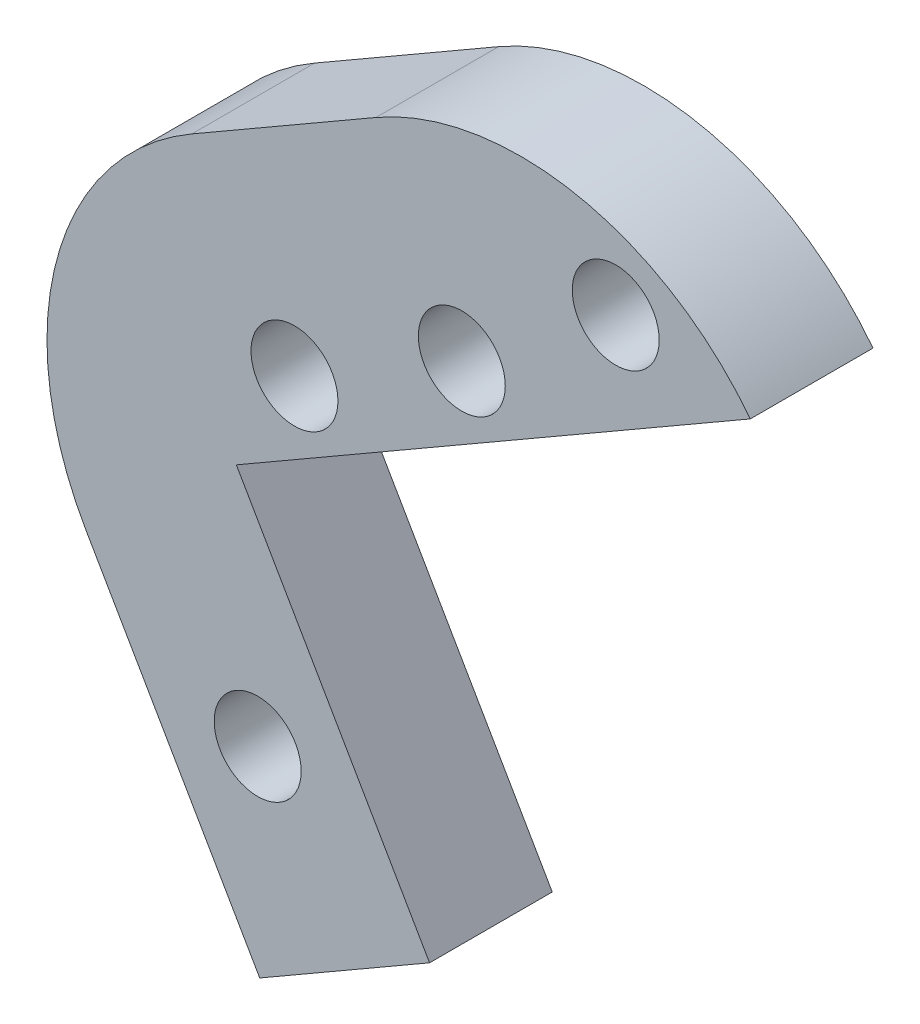
SolidWorks part; units mm, degrees
material "Erable"
ref_plane "Plan de face" through (0, 0, 0) normal (0, 0, 1) x (1, 0, 0)
ref_plane "Plan de dessus" through (0, 0, 0) normal (0, 1, 0) x (1, 0, 0)
ref_plane "Plan de droite" through (0, 0, 0) normal (1, 0, 0) x (0, 0, -1)
sketch "Esquisse3" plane through (0, 0, 0) normal (0, 0, 1) x (1, 0, 0)
  line L0 (0, -3.4925) -> (0, 3.4925) construction
  line L1 (-54.6725, 55) -> (54.6725, 55)
  line L2 (-77.5, 12.5385) -> (-77.5, -12.5385)
  line L3 (-54.6725, -55) -> (54.6725, -55)
  line L4 (77.5, 12.5385) -> (77.5, -12.5385)
  line L5 (3.4925, 0) -> (-3.4925, 0) construction
  line L6 (-54.6725, 55) -> (-71.993, 85)
  line L7 (-71.993, 85) -> (-107.5, 64.5)
  line L8 (-107.5, 64.5) -> (-77.5, 12.5385)
  line L9 (-77.5, -12.5385) -> (-107.5, -64.5)
  line L10 (-107.5, -64.5) -> (-71.993, -85)
  line L11 (-71.993, -85) -> (-54.6725, -55)
  line L12 (54.6725, 55) -> (71.993, 85)
  line L13 (71.993, 85) -> (107.5, 64.5)
  line L14 (107.5, 64.5) -> (77.5, 12.5385)
  line L15 (77.5, -12.5385) -> (107.5, -64.5)
  line L16 (107.5, -64.5) -> (71.993, -85)
  line L17 (71.993, -85) -> (54.6725, -55)
  line L19 (-26.875, 36.6667) -> (26.875, 36.6667)
  line L20 (-26.875, 36.6667) -> (-26.875, -36.6667)
  line L21 (-26.875, -36.6667) -> (26.875, -36.6667)
  line L22 (26.875, 36.6667) -> (26.875, -36.6667)
  point P4 (0, 55)
  point P7 (-77.5, 0)
  point P24 (0, -36.6667)
  point P27 (26.875, 0)
  dimension "D3" = 120
  dimension "D6" = 41
  dimension "D7" = 120
  dimension "D8" = 120
  dimension "D9" = 120
  dimension "D2" = 110
  dimension "D10" = 53.75
  dimension "D11" = 73.3333
  dimension "D4" = 170
  dimension "D5" = 215
  dimension "D12" = 60
extrude "Boss.-Extru.2" add sketch "Esquisse3" against normal blind 6.35 separate body
fillet "Congé6" radius 20 12 edges at (77.5, -12.5385, -3.175) (77.5, 12.5385, -3.175) (54.6725, 55, -3.175) (-54.6725, 55, -3.175) (-77.5, 12.5385, -3.175) (-77.5, -12.5385, -3.175) (-54.6725, -55, -3.175) (54.6725, -55, -3.175) (26.875, -36.6667, -3.175) (26.875, 36.6667, -3.175) (-26.875, -36.6667, -3.175) (-26.875, 36.6667, -3.175)
fillet "Congé7" radius 15 8 edges at (71.993, -85, -3.175) (107.5, -64.5, -3.175) (107.5, 64.5, -3.175) (71.993, 85, -3.175) (-71.993, 85, -3.175) (-107.5, 64.5, -3.175) (-71.993, -85, -3.175) (-107.5, -64.5, -3.175)
sketch "Esquisse4" plane through (0, 0, 0) normal (0, 0, 1) x (1, 0, 0)
  line L0 (-53.2831, 32.2936) -> (-74.2831, 68.6667)
  line L1 (-74.2831, 68.6667) -> (-92.2098, 58.3167)
  line L2 (-92.2098, 58.3167) -> (-71.2098, 21.9436)
  line L3 (-71.2098, 21.9436) -> (-53.2831, 32.2936)
  line L4 (-83.2465, 63.4917) -> (-89.7465, 74.75) construction
  line L5 (-84.9833, 77.5) -> (-94.5096, 72) construction
  line L6 (-60.446, 65) -> (-64.493, 72.0096) construction
  line L7 (-49.7465, 5.468) -> (-52.7465, 10.6641) construction
  line L8 (-51.695, 4.343) -> (-54.695, 9.5391)
  line L9 (-47.7979, 6.593) -> (-50.7979, 11.7891)
  line L10 (-56.2914, 26.804) -> (-80.5414, 68.8063) construction
  line L11 (-80.5414, 68.8063) -> (-89.2016, 63.8063) construction
  line L12 (-89.2016, 63.8063) -> (-64.9516, 21.804) construction
  line L13 (-64.9516, 21.804) -> (-56.2914, 26.804) construction
  line L14 (-81.7098, 40.1301) -> (-77.0766, 42.8051) construction
  arc A0 (-51.695, 4.343) -> (-47.7979, 6.593) centre (-49.7465, 5.468) ccw
  arc A1 (-50.7979, 11.7891) -> (-54.695, 9.5391) centre (-52.7465, 10.6641) ccw
  circle A3 centre (-56.2914, 26.804) radius 2.25
  circle A4 centre (-64.9516, 21.804) radius 2.25
  circle A5 centre (-89.2016, 63.8063) radius 2.25
  circle A6 centre (-80.5414, 68.8063) radius 2.25
  point P12 (-51.2465, 8.066)
  point P23 (-84.8715, 66.3063)
  dimension "D5" = 2.25
  dimension "D7" = 48.5
  dimension "D9" = 4.5
  dimension "D1" = 20.7
  dimension "D2" = 42
  dimension "D3" = 13
  dimension "D4" = 19
  dimension "D6" = 6
  dimension "D8" = 10
extrude "Enlèv. mat.-Extru.2" cut sketch "Esquisse4" against normal blind 6.35
mirror "Symétrie1" about plane through (0, 0, 0) normal (0, 1, 0) of "Enlèv. mat.-Extru.2"
mirror "Symétrie2" about plane through (0, 0, 0) normal (1, 0, 0) of "Symétrie1", "Enlèv. mat.-Extru.2"
sketch "Esquisse5" plane through (0, 0, 0) normal (0, 0, 1) x (1, 0, 0)
  line L0 (0, -3.4925) -> (0, 3.4925) construction
  line L1 (-33, 48) -> (33, 48) construction
  line L2 (-33, 48) -> (-33, -48) construction
  line L3 (-33, -48) -> (33, -48) construction
  line L4 (33, 48) -> (33, -48) construction
  line L5 (3.4925, 0) -> (-3.4925, 0) construction
  point P6 (0, 48)
  point P7 (-33, 0)
  dimension "D1" = 66
  dimension "D2" = 96
hole_wizard "Diamètre du perçage Ø4.0 (4)1" positions "Esquisse6" profile "Esquisse7" hole size "Ø4.0" standard "Ansi Metric" end condition through all
sketch "Esquisse6" plane through (0, 0, 0) normal (0, 0, 1) x (1, 0, 0)
  point P0 (33, 48)
  point P3 (-33, 48)
  point P6 (-33, -48)
  point P9 (33, -48)
sketch "Esquisse7" plane through (33, 48, 0) normal (1, 0, 0) x (0, -1, 0)
  line L0 (0, 0) -> (0, 6.35)
  line L1 (0, 6.35) -> (2, 6.35)
  line L2 (2, 6.35) -> (2, 0)
  line L5 (2, 0) -> (0, 0)
  line L11 (0, -6.35) -> (0, 107.95) construction
  dimension "Diamètre du perçage jusqu'au prochain" = 4
  dimension "Profondeur du perçage jusqu'au prochain" = 6.35
sketch "Esquisse8" plane through (0, 0, 0) normal (0, 0, 1) x (1, 0, 0)
  line L1 (-102.0096, 79.5096) -> (102.0096, 79.5096) construction
  line L2 (-102.0096, 79.5096) -> (-102.0096, -79.5096) construction
  line L3 (-102.0096, -79.5096) -> (102.0096, -79.5096) construction
  line L4 (102.0096, 79.5096) -> (102.0096, -79.5096) construction
  arc A0 (94.5096, -72) -> (100, -51.5096) centre (87.0096, -59.0096) ccw construction
  arc A1 (64.493, -72.0096) -> (84.9833, -77.5) centre (77.4833, -64.5096) ccw construction
  arc A2 (-64.493, 72.0096) -> (-84.9833, 77.5) centre (-77.4833, 64.5096) ccw construction
  arc A3 (-94.5096, 72) -> (-100, 51.5096) centre (-87.0096, 59.0096) ccw construction
  dimension "D1" = 204.0192
  dimension "D2" = 159.0192
sketch "Esquisse9" plane through (0, 0, 0) normal (0, 0, 1) x (1, 0, 0)
  line L0 (-65.6089, 73.6747) -> (-92.2098, 58.3167)
  line L1 (-92.2098, 58.3167) -> (-82.2098, 40.9962)
  line L2 (-92.2098, 58.3167) -> (-71.2098, 21.9436) construction
  line L3 (-82.2098, 40.9962) -> (-91, 35.9212)
  line L4 (-100, 51.5096) -> (-80.1795, 17.1795) construction
  line L5 (-91, 35.9212) -> (-100, 51.5096)
  line L6 (-84.9833, 77.5) -> (-94.5096, 72) construction
  line L7 (-84.9833, 77.5) -> (-94.5096, 72)
  line L8 (-74.2831, 68.6667) -> (-92.2098, 58.3167) construction
  arc A0 (-94.5096, 72) -> (-100, 51.5096) centre (-87.0096, 59.0096) ccw construction
  arc A1 (-94.5096, 72) -> (-100, 51.5096) centre (-87.0096, 59.0096) ccw
  arc A2 (-64.493, 72.0096) -> (-84.9833, 77.5) centre (-77.4833, 64.5096) ccw construction
  arc A3 (-65.6089, 73.6747) -> (-84.9833, 77.5) centre (-77.4833, 64.5096) ccw
  dimension "D1" = 20
extrude "Enlèv. mat.-Extru.3" cut sketch "Esquisse9" against normal through all flip side to cut
sketch "Esquisse10" plane through (0, 0, 0) normal (0, 0, 1) x (1, 0, 0)
  line L0 (-91.1049, 46.2529) -> (-86.6049, 38.4587) construction
  line L1 (-91, 35.9212) -> (-82.2098, 40.9962) construction
  line L2 (-65.6089, 73.6747) -> (-92.2098, 58.3167) construction
  circle A0 centre (-91.1049, 46.2529) radius 2.25
  circle A1 centre (-72.574, 74.8496) radius 2.25
  circle A2 centre (-80.5414, 68.8063) radius 2.25 construction
  point P11 (-72.2159, 74.4406)
  dimension "D1" = 4.5
  dimension "D2" = 9
  dimension "D3" = 4.5
  dimension "D4" = 10
extrude "Enlèv. mat.-Extru.4" cut sketch "Esquisse10" against normal through all
equation "\"D10@Esquisse3\"=\"D5@Esquisse3\"/4"
equation "\"D11@Esquisse3\"=\"D2@Esquisse3\"/1.5"
